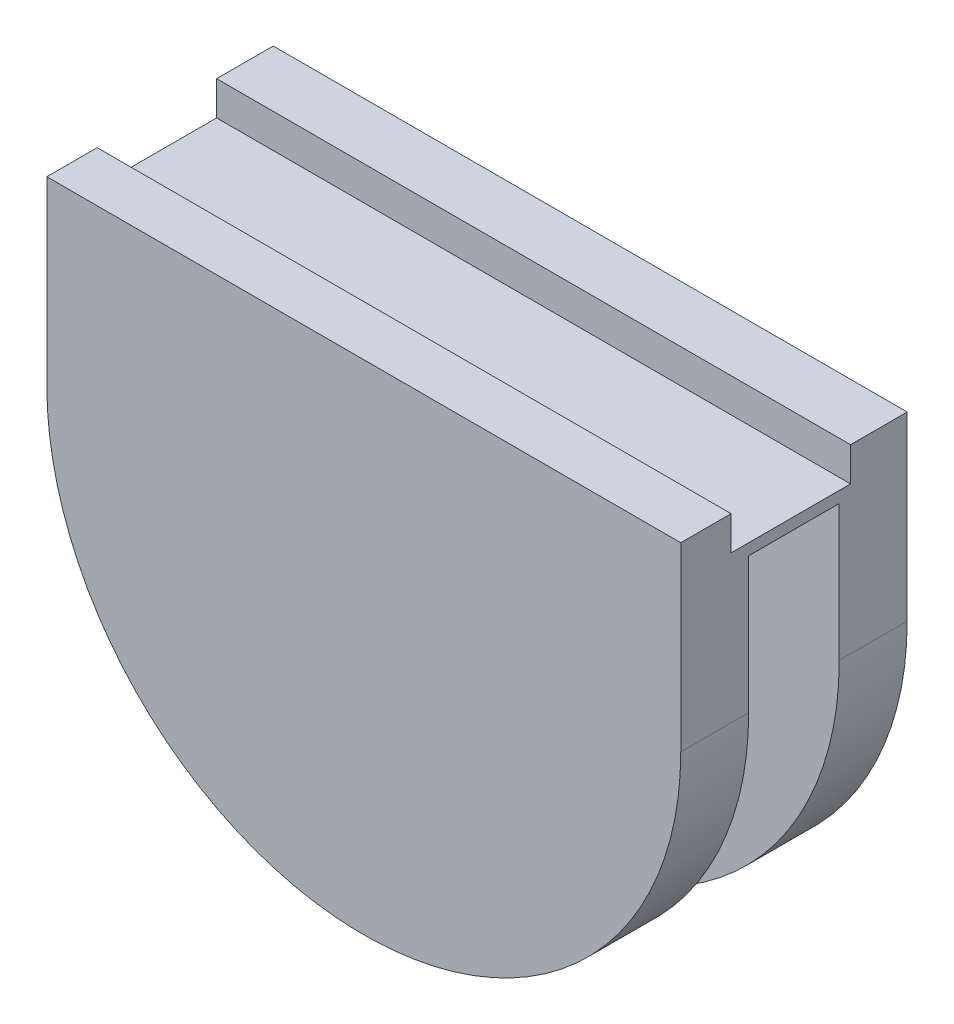
SolidWorks part; units mm, degrees
ref_plane "Front Plane" through (0, 0, 0) normal (0, 0, 1) x (1, 0, 0)
ref_plane "Top Plane" through (0, 0, 0) normal (0, 1, 0) x (1, 0, 0)
ref_plane "Right Plane" through (0, 0, 0) normal (1, 0, 0) x (0, 0, -1)
sketch "Sketch1" plane through (0, 0, 0) normal (0, 0, 1) x (1, 0, 0)
  line L0 (-26.0745, 2.892) -> (1.9255, 2.892)
  line L1 (1.9255, 2.892) -> (1.9255, -5.108)
  line L3 (-26.0745, -5.108) -> (-26.0745, 2.892)
  arc A0 (-26.0745, -5.108) -> (1.9255, -5.108) centre (-12.0745, -5.108) ccw
  dimension "D1" = 8
  dimension "D2" = 28
extrude "Boss-Extrude1" add sketch "Sketch1" along normal blind 3
sketch "Sketch2" plane through (0, 0, 0) normal (0, 0, -1) x (-1, 0, 0)
  line L0 (-1.9255, 2.892) -> (-1.9255, 0.892)
  line L1 (-1.9255, -5.108) -> (-1.9255, 2.892) construction
  line L2 (-1.9255, 0.892) -> (26.0745, 0.892)
  line L3 (26.0745, 2.892) -> (26.0745, -5.108) construction
  line L4 (26.0745, 0.892) -> (26.0745, 2.892)
  line L5 (26.0745, 2.892) -> (-1.9255, 2.892)
  dimension "D1" = 2
extrude "Boss-Extrude2" add sketch "Sketch2" along normal blind 4
sketch "Sketch3" plane through (0, 0, -4) normal (0, 0, -1) x (-1, 0, 0)
  line L0 (-1.9255, 2.892) -> (26.0745, 2.892)
  line L1 (26.0745, 2.892) -> (26.0745, -5.108)
  line L3 (-1.9255, -5.108) -> (-1.9255, 2.892)
  arc A2 (-1.9255, -5.108) -> (26.0745, -5.108) centre (12.0745, -5.108) ccw
extrude "Boss-Extrude3" add sketch "Sketch3" along normal blind 3
sketch "Sketch4" plane through (0, 2.892, 0) normal (0, 1, 0) x (1, 0, 0)
  line L0 (1.9255, 4.5) -> (1.9255, -0.7769)
  line L1 (1.9255, -3) -> (1.9255, 7) construction
  line L2 (1.9255, -0.7769) -> (-26.0745, -0.7769)
  line L3 (-26.0745, -3) -> (-26.0745, 7) construction
  line L4 (-26.0745, -0.7769) -> (-26.0745, 4.5)
  line L5 (-26.0745, 4.5) -> (1.9255, 4.5)
  dimension "D1" = 2.5
extrude "Cut-Extrude1" cut sketch "Sketch4" against normal blind 1.5
